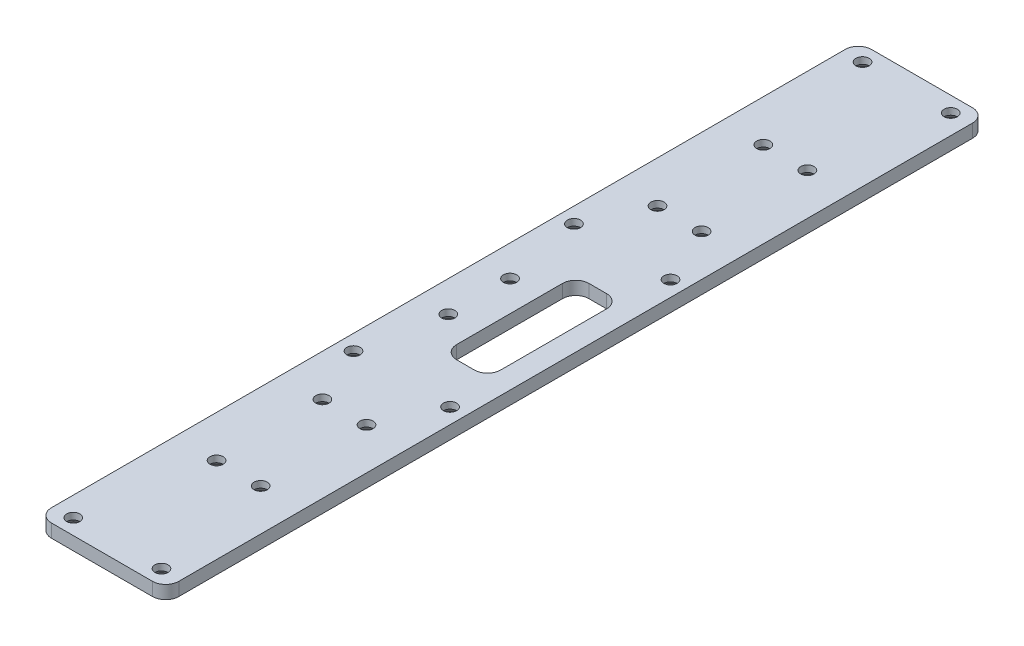
SolidWorks part; units mm, degrees
material "Thornel Mat VMA"
ref_plane "前视基准面" through (0, 0, 0) normal (0, 0, 1) x (1, 0, 0)
ref_plane "上视基准面" through (0, 0, 0) normal (0, 1, 0) x (1, 0, 0)
ref_plane "右视基准面" through (0, 0, 0) normal (1, 0, 0) x (0, 0, -1)
sketch "草图1" plane through (0, 0, 0) normal (0, 1, 0) x (1, 0, 0)
  line L1 (-14.45, -93) -> (14.45, -93)
  line L2 (-14.45, -93) -> (-14.45, 93)
  line L3 (-14.45, 93) -> (14.45, 93)
  line L4 (14.45, -93) -> (14.45, 93)
  line L5 (-14.45, -93) -> (14.45, 93) construction
  line L6 (-14.45, 93) -> (14.45, -93) construction
  point P0 (0, 0)
  dimension "D1" = 28.9
  dimension "D2" = 186
extrude "凸台-拉伸1" add sketch "草图1" along normal blind 3
fillet "圆角1" radius 3 4 edges at (14.45, 1.5, -93) (-14.45, 1.5, -93) (-14.45, 1.5, 93) (14.45, 1.5, 93)
sketch "草图2" plane through (0, 3, 0) normal (0, 1, 0) x (1, 0, 0)
  line L0 (-14.45, 0) -> (14.45, 0) construction
  line L1 (-14.45, 90) -> (-14.45, -90) construction
  line L2 (14.45, -90) -> (14.45, 90) construction
  line L3 (0, -93) -> (0, 0) construction
  line L4 (-11.45, -93) -> (11.45, -93) construction
  line L5 (-5, 38) -> (5, 62) construction
  line L6 (-5, -62) -> (5, -62) construction
  line L7 (-5, -62) -> (-5, -38) construction
  line L8 (-5, -38) -> (5, -38) construction
  line L9 (5, -62) -> (5, -38) construction
  line L10 (-5, -62) -> (5, -38) construction
  line L11 (-5, -38) -> (5, -62) construction
  line L12 (-5, 62) -> (5, 38) construction
  line L13 (5, 62) -> (5, 38) construction
  line L14 (-5, 38) -> (5, 38) construction
  line L15 (-5, 62) -> (-5, 38) construction
  line L16 (-5, 62) -> (5, 62) construction
  circle A0 centre (-10, -89.5) radius 1.5
  circle A1 centre (10, -89.5) radius 1.5
  circle A2 centre (10, 89.5) radius 1.5
  circle A3 centre (-10, 89.5) radius 1.5
  circle A4 centre (-5, -38) radius 1.5
  circle A5 centre (-5, -62) radius 1.5
  circle A6 centre (5, -38) radius 1.5
  circle A7 centre (5, -62) radius 1.5
  circle A8 centre (5, 62) radius 1.5
  circle A9 centre (5, 38) radius 1.5
  circle A10 centre (-5, 62) radius 1.5
  circle A11 centre (-5, 38) radius 1.5
  circle A12 centre (-7.45, -7) radius 1.5
  circle A13 centre (-7.45, 7) radius 1.5
  circle A14 centre (10.95, 25) radius 1.5
  circle A15 centre (10.95, -25) radius 1.5
  circle A16 centre (-10.95, -25) radius 1.5
  circle A17 centre (-10.95, 25) radius 1.5
  point P19 (0, -50)
  point P36 (0, 50)
  dimension "D3" = 3
  dimension "D7" = 3
  dimension "D8" = 3
  dimension "D11" = 3
  dimension "D9" = 7
  dimension "D13" = 3
  dimension "D1" = 10
  dimension "D2" = 3.5
  dimension "D4" = 31
  dimension "D5" = 10
  dimension "D6" = 24
  dimension "D10" = 7
  dimension "D12" = 3.5
  dimension "D14" = 25
extrude "切除-拉伸1" cut sketch "草图2" against normal blind 3
chamfer "倒角1" distance 1.5 angle 45 18 edges at (-10, 0, -91) (10, 0, -88) (-10, 0, 91) (10, 0, 88) (5, 0, -60.5) (-5, 0, -63.5) (5, 0, -36.5) (-5, 0, -39.5) (-7.45, 0, -8.5) (-7.45, 0, 8.5) (5, 0, 36.5) (-5, 0, 39.5) (5, 0, 60.5) (-5, 0, 63.5) (10.95, 0, -23.5) (-10.95, 0, -26.5) (-10.95, 0, 26.5) (10.95, 0, 23.5)
sketch "草图3" plane through (0, 3, 0) normal (0, 1, 0) x (1, 0, 0)
  line L0 (-14.45, 0) -> (14.45, 0) construction
  line L1 (-14.45, 90) -> (-14.45, -90) construction
  line L2 (14.45, -90) -> (14.45, 90) construction
  line L4 (-0.55, -15) -> (9.45, -15)
  line L5 (-0.55, -15) -> (-0.55, 15)
  line L6 (-0.55, 15) -> (9.45, 15)
  line L7 (9.45, -15) -> (9.45, 15)
  line L8 (-0.55, -15) -> (9.45, 15) construction
  line L9 (-0.55, 15) -> (9.45, -15) construction
  point P6 (4.45, 0)
  dimension "D1" = 5
  dimension "D2" = 10
  dimension "D3" = 30
extrude "切除-拉伸2" cut sketch "草图3" against normal blind 3
fillet "圆角2" radius 3 4 edges at (-0.55, 1.5, 15) (9.45, 1.5, 15) (9.45, 1.5, -15) (-0.55, 1.5, -15)
